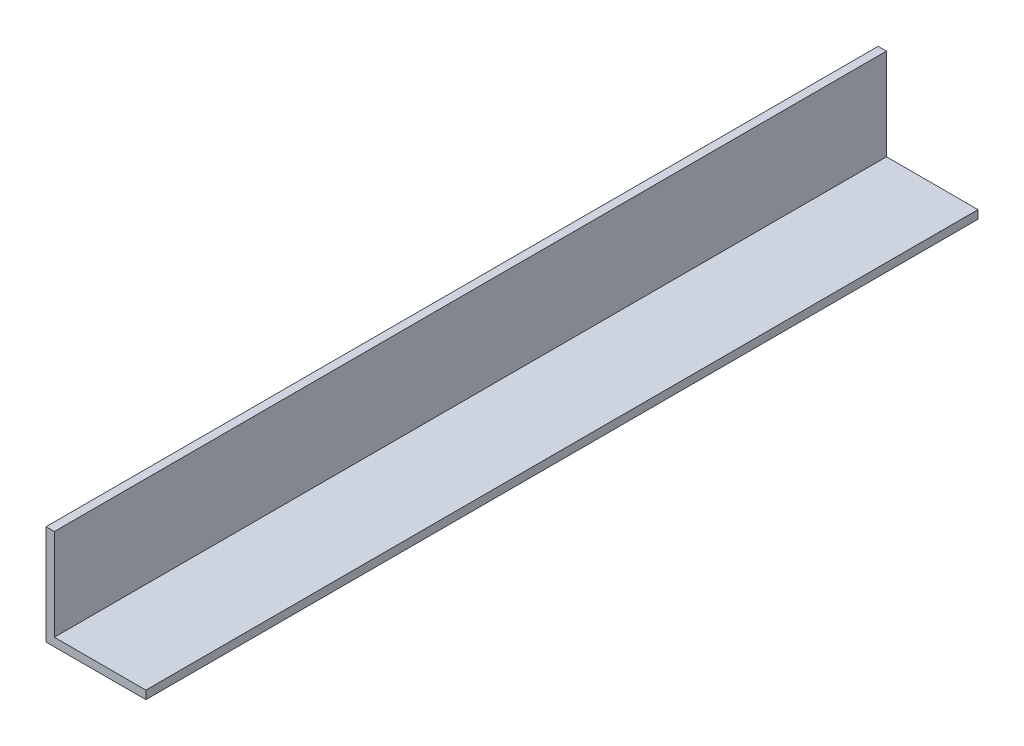
SolidWorks part; units mm, degrees
ref_plane "Alzado" through (0, 0, 0) normal (0, 0, 1) x (1, 0, 0)
ref_plane "Planta" through (0, 0, 0) normal (0, 1, 0) x (1, 0, 0)
ref_plane "Vista lateral" through (0, 0, 0) normal (1, 0, 0) x (0, 0, -1)
sketch "Croquis1" plane through (0, 0, 0) normal (0, 0, 1) x (1, 0, 0)
  line L0 (-3, 3) -> (-3, -3)
  line L1 (-3, -3) -> (3, -3)
  line L2 (3, -3) -> (3, -2.5)
  line L3 (3, -2.5) -> (-2.5, -2.5)
  line L4 (-2.5, -2.5) -> (-2.5, 3)
  line L5 (-2.5, 3) -> (-3, 3)
  line L6 (0, -55) -> (0, 55) construction
  line L7 (55, 0) -> (-55, 0) construction
  point P6 (0, -3)
  point P7 (-3, 0)
  dimension "D1" = 0.5
  dimension "D2" = 0.5
  dimension "D3" = 6
  dimension "D4" = 6
extrude "Saliente-Extruir1" add sketch "Croquis1" along normal blind 50
